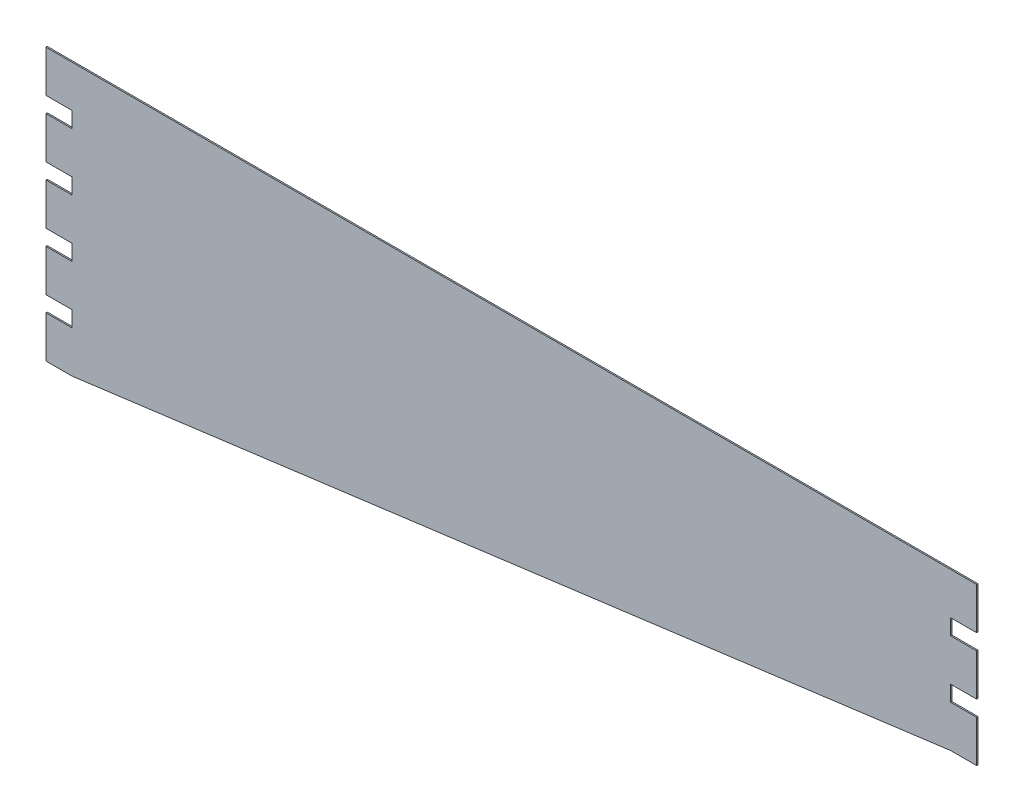
SolidWorks part; units mm, degrees
material "Hexcel AS4C (3000 Filaments)"
ref_plane "Front Plane" through (0, 0, 0) normal (0, 0, 1) x (1, 0, 0)
ref_plane "Top Plane" through (0, 0, 0) normal (0, 1, 0) x (1, 0, 0)
ref_plane "Right Plane" through (0, 0, 0) normal (1, 0, 0) x (0, 0, -1)
sketch "Sketch2" plane through (0, 0, 0) normal (0, 0, 1) x (1, 0, 0)
  line L0 (0, 0) -> (5, 0)
  line L1 (5, 0) -> (173, 22)
  line L2 (173, 22) -> (178, 22)
  line L3 (178, 22) -> (178, 52)
  line L4 (178, 52) -> (0, 52)
  line L5 (0, 52) -> (0, 0)
  dimension "D1" = 52
  dimension "D2" = 5
  dimension "D3" = 5
  dimension "D4" = 168
  dimension "D5" = 30
extrude "Boss-Extrude1" add sketch "Sketch2" along normal mid plane 0.25
sketch "Sketch4" plane through (0, 0, 0.125) normal (0, 0, 1) x (1, 0, 0)
  line L0 (178, 22) -> (178, 52) construction
  line L1 (178, 44) -> (173, 44)
  line L2 (178, 44) -> (178, 41)
  line L3 (178, 41) -> (173, 41)
  line L4 (173, 44) -> (173, 41)
  line L5 (178, 52) -> (0, 52) construction
  dimension "D1" = 5
  dimension "D2" = 3
  dimension "D3" = 8
extrude "Cut-Extrude2" cut sketch "Sketch4" against normal through all
pattern_linear "LPattern3" count 4 spacing 11 along (0, -1, 0) count 2 spacing 173 along (-1, 0, 0) of "Cut-Extrude2"
